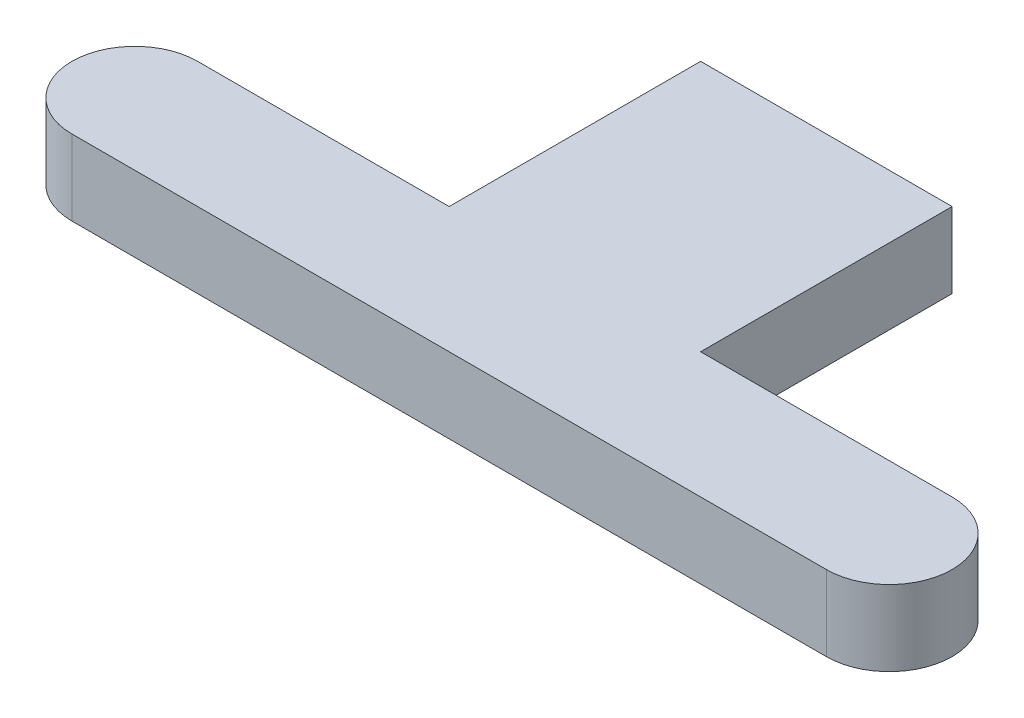
SolidWorks part; units mm, degrees
ref_plane "Front Plane" through (0, 0, 0) normal (0, 0, 1) x (1, 0, 0)
ref_plane "Top Plane" through (0, 0, 0) normal (0, 1, 0) x (1, 0, 0)
ref_plane "Right Plane" through (0, 0, 0) normal (1, 0, 0) x (0, 0, -1)
sketch "Sketch1" plane through (0, 0, 0) normal (0, 1, 0) x (1, 0, 0)
  line L1 (-7.5, 0) -> (22.5, 0)
  line L3 (-7.5, 5) -> (22.5, 5)
  arc A0 (-7.5, 5) -> (-7.5, 0) centre (-7.5, 2.5) ccw
  arc A1 (22.5, 0) -> (22.5, 5) centre (22.5, 2.5) ccw
  dimension "D2" = 2.5
  dimension "D1" = 30
extrude "Boss-Extrude1" add sketch "Sketch1" along normal blind 3
sketch "Sketch2" plane through (0, 0, 0) normal (0, -1, 0) x (1, 0, 0)
  line L4 (-7.5, -4) -> (22.5, -4)
  line L5 (22.5, -1) -> (-7.5, -1)
  line L6 (-7.5, -4) -> (22.5, -4)
  line L7 (22.5, -1) -> (-7.5, -1)
  arc A4 (-7.5, -1) -> (-7.5, -4) centre (-7.5, -2.5) ccw
  arc A5 (22.5, -4) -> (22.5, -1) centre (22.5, -2.5) ccw
  arc A6 (-7.5, -1) -> (-7.5, -4) centre (-7.5, -2.5) ccw
  arc A7 (22.5, -4) -> (22.5, -1) centre (22.5, -2.5) ccw
  dimension "D1" = 1
extrude "Cut-Extrude1" cut sketch "Sketch2" against normal blind 1.5
sketch "Sketch4" plane through (0, 0, -5) normal (0, 0, -1) x (-1, 0, 0)
  line L0 (-22.5, 3) -> (7.5, 3) construction
  line L1 (-12.5, 3) -> (-2.5, 3)
  line L2 (-12.5, 3) -> (-12.5, 0)
  line L3 (-12.5, 0) -> (-2.5, 0)
  line L4 (-2.5, 3) -> (-2.5, 0)
  line L5 (-22.5, 0) -> (7.5, 0) construction
  point P8 (-7.5, 3)
  dimension "D1" = 10
extrude "Boss-Extrude3" add sketch "Sketch4" along normal blind 10
